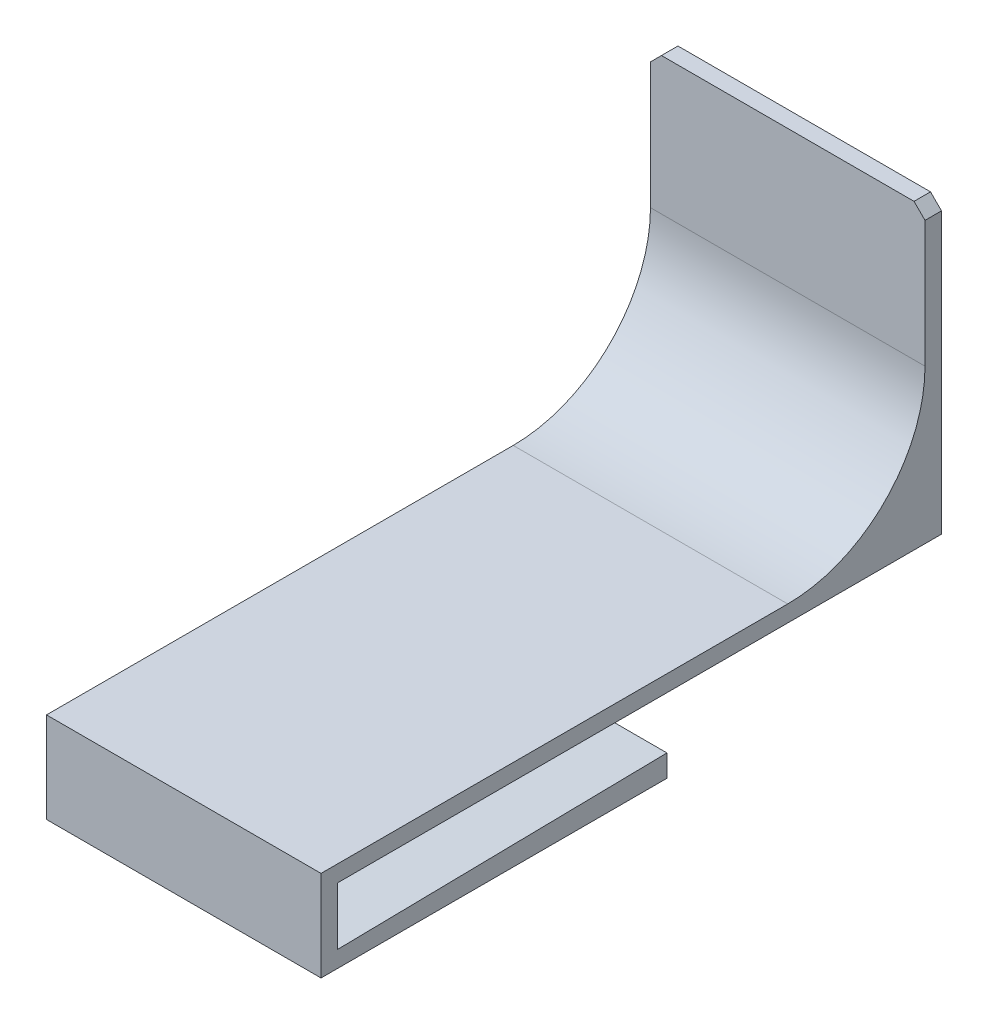
SolidWorks part; units mm, degrees
ref_plane "Plano frontal" through (0, 0, 0) normal (0, 0, 1) x (1, 0, 0)
ref_plane "Plano superior" through (0, 0, 0) normal (0, 1, 0) x (1, 0, 0)
ref_plane "Plano direito" through (0, 0, 0) normal (1, 0, 0) x (0, 0, -1)
sketch "Esboço1" plane through (0, 0, 0) normal (1, 0, 0) x (0, 0, -1)
  line L0 (0, 0) -> (-63, 0)
  line L1 (-63, 0) -> (-63, 16.5)
  line L2 (-63, 16.5) -> (22, 16.5)
  line L3 (47, 41.5) -> (47, 66.5)
  line L4 (0, 0) -> (0, 3)
  line L5 (0, 3) -> (-60, 3) construction
  line L6 (-60, 3) -> (-60, 13.5)
  line L7 (-60, 13.5) -> (50, 13.5)
  line L8 (50, 13.5) -> (50, 66.5)
  line L9 (50, 66.5) -> (47, 66.5)
  line L10 (-60, 3) -> (0, 4)
  line L11 (0, 4) -> (0, 3)
  arc A0 (22, 16.5) -> (47, 41.5) centre (22, 41.5) ccw
  point P16 (47, 16.5)
  dimension "D9" = 25
  dimension "D1" = 10.5
  dimension "D2" = 60
  dimension "D3" = 3
  dimension "D4" = 3
  dimension "D5" = 3
  dimension "D6" = 3
  dimension "D7" = 50
  dimension "D8" = 110
  dimension "D10" = 9.5
extrude "Ressalto-extrusão1" add sketch "Esboço1" along normal mid plane 50
chamfer "Chanfro1" distance 2 angle 45 2 edges at (-25, 66.5, -48.5) (25, 66.5, -48.5)
